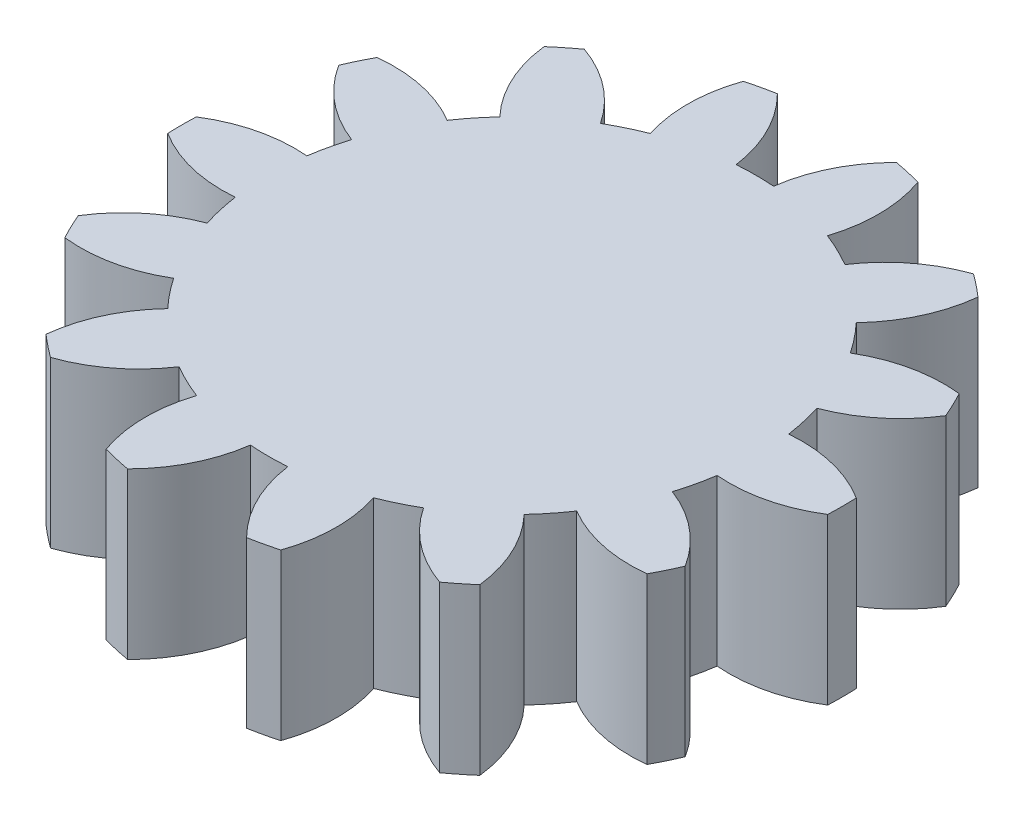
SolidWorks part; units mm, degrees
ref_plane "前视基准面" through (0, 0, 0) normal (0, 0, 1) x (1, 0, 0)
ref_plane "上视基准面" through (0, 0, 0) normal (0, 1, 0) x (1, 0, 0)
ref_plane "右视基准面" through (0, 0, 0) normal (1, 0, 0) x (0, 0, -1)
other "Configuration Table"
sketch "草图1" plane through (0, 0, 0) normal (0, 1, 0) x (1, 0, 0)
  circle A0 centre (0, 0) radius 20
  dimension "D1" = 40
extrude "凸台-拉伸1" add sketch "草图1" along normal blind 10
sketch "草图2" plane through (0, 10, 0) normal (0, 1, 0) x (1, 0, 0)
  line L0 (0, 0) -> (0, 24.737) construction
  line L1 (0, 0) -> (2.9658, 26.3221)
  line L2 (1.9594, 17.39) -> (23.8386, 14.9248)
  line L3 (1.9594, 17.39) -> (17.5126, 9.6596)
  circle A0 centre (0, 0) radius 17.5
  circle A1 centre (0, 0) radius 20
  circle A2 centre (0, 0) radius 20
  circle A3 centre (0, 0) radius 14.75
  circle A4 centre (9.736, 13.5248) radius 8.6842
  circle A5 centre (-9.736, 13.5248) radius 8.6842
  dimension "D2" = 35
  dimension "D3" = 29.5
  dimension "D4" = 6.429
  dimension "D5" = 20
  dimension "D1" = 0
extrude "切除-拉伸1" cut sketch "草图2" against normal through all both and the other way through all contours A0 L0 A2 A5 | L0 A0 L1 L3 | A4 A2 L1 | A3 L0 A0 A5 | L0 A3 A4 A0
pattern_circular "阵列(圆周)1" count 14 over 360 about axis through (0, 0, 0) along (0, 1, 0) of "切除-拉伸1"
